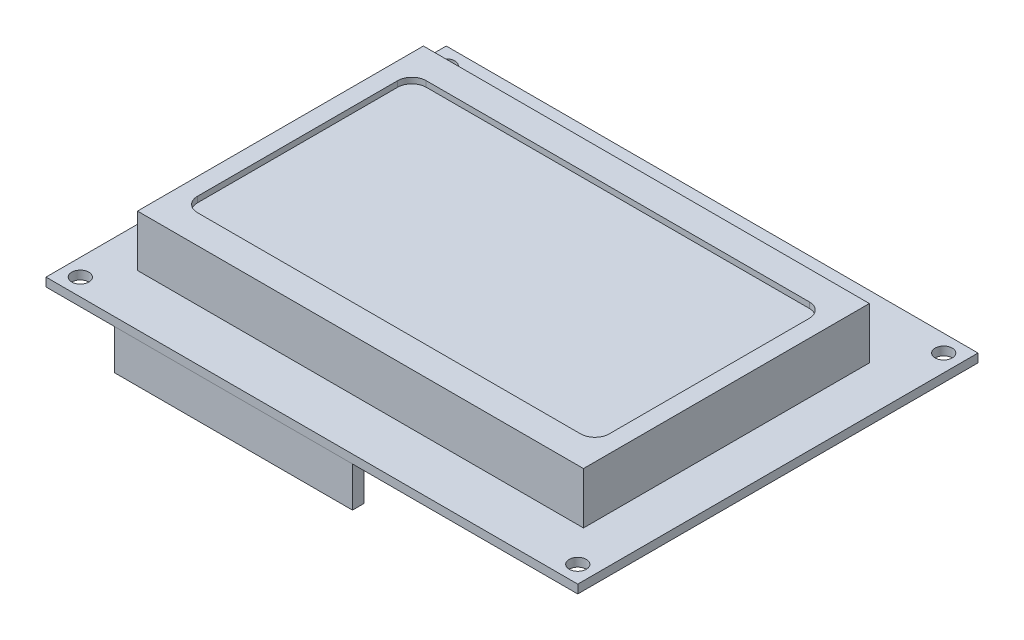
SolidWorks part; units mm, degrees
material "Alloy Steel"
ref_plane "Спереди" through (0, 0, 0) normal (0, 0, 1) x (1, 0, 0)
ref_plane "Сверху" through (0, 0, 0) normal (0, 1, 0) x (1, 0, 0)
ref_plane "Справа" through (0, 0, 0) normal (1, 0, 0) x (0, 0, -1)
sketch "Sketch1" plane through (0, 0, 0) normal (0, 1, 0) x (1, 0, 0)
  line L1 (0, 0) -> (93, 0)
  line L2 (0, 0) -> (0, 70)
  line L3 (0, 70) -> (93, 70)
  line L4 (93, 0) -> (93, 70)
  dimension "D1" = 93
  dimension "D2" = 70
extrude "Boss-Extrude1" add sketch "Sketch1" along normal blind 1.5
sketch "Sketch2" plane through (0, 1.5, 0) normal (0, 1, 0) x (1, 0, 0)
  line L0 (93, 0) -> (93, 70) construction
  line L1 (7, 9) -> (85, 9)
  line L2 (7, 9) -> (7, 59)
  line L3 (7, 59) -> (85, 59)
  line L4 (85, 9) -> (85, 59)
  line L5 (0, 0) -> (93, 0) construction
  dimension "D1" = 78
  dimension "D2" = 50
  dimension "D3" = 8
  dimension "D4" = 9
extrude "Boss-Extrude2" add sketch "Sketch2" along normal blind 9
sketch "Sketch3" plane through (0, 10.5, 0) normal (0, 1, 0) x (1, 0, 0)
  line L0 (85, 59) -> (7, 59) construction
  line L1 (12.5, 54) -> (79.5, 54)
  line L2 (10, 51.5) -> (10, 16.5)
  line L3 (12.5, 14) -> (79.5, 14)
  line L4 (82, 51.5) -> (82, 16.5)
  line L5 (7, 9) -> (85, 9) construction
  line L6 (7, 59) -> (7, 9) construction
  line L7 (85, 9) -> (85, 59) construction
  arc A0 (79.5, 54) -> (82, 51.5) centre (79.5, 51.5) cw
  arc A1 (82, 16.5) -> (79.5, 14) centre (79.5, 16.5) cw
  arc A2 (12.5, 14) -> (10, 16.5) centre (12.5, 16.5) cw
  arc A3 (10, 51.5) -> (12.5, 54) centre (12.5, 51.5) cw
  dimension "D5" = 2.5
  dimension "D1" = 5
  dimension "D2" = 5
  dimension "D3" = 3
  dimension "D4" = 3
extrude "Cut-Extrude1" cut sketch "Sketch3" against normal blind 1
sketch "Sketch4" plane through (0, 1.5, 0) normal (0, 1, 0) x (1, 0, 0)
  line L0 (0, 70) -> (0, 0) construction
  line L1 (0, 0) -> (93, 0) construction
  line L2 (93, 70) -> (0, 70) construction
  line L3 (93, 0) -> (93, 70) construction
  circle A0 centre (3, 67) radius 1.5
  circle A1 centre (90, 67) radius 1.5
  circle A2 centre (90, 3) radius 1.5
  circle A3 centre (3, 3) radius 1.5
  dimension "D1" = 3
  dimension "D2" = 3
  dimension "D3" = 3
  dimension "D4" = 3
  dimension "D5" = 3
extrude "Cut-Extrude2" cut sketch "Sketch4" against normal through all
sketch "Sketch5" plane through (0, 0, 0) normal (0, -1, 0) x (1, 0, 0)
  line L0 (0, 0) -> (93, 0) construction
  line L1 (12, 0) -> (53.6, 0)
  line L2 (12, 0) -> (12, -2)
  line L3 (12, -2) -> (53.6, -2)
  line L4 (53.6, 0) -> (53.6, -2)
  line L5 (0, -70) -> (0, 0) construction
  dimension "D1" = 2
  dimension "D2" = 12
  dimension "D3" = 41.6
extrude "Boss-Extrude3" add sketch "Sketch5" along normal blind 7 separate body
